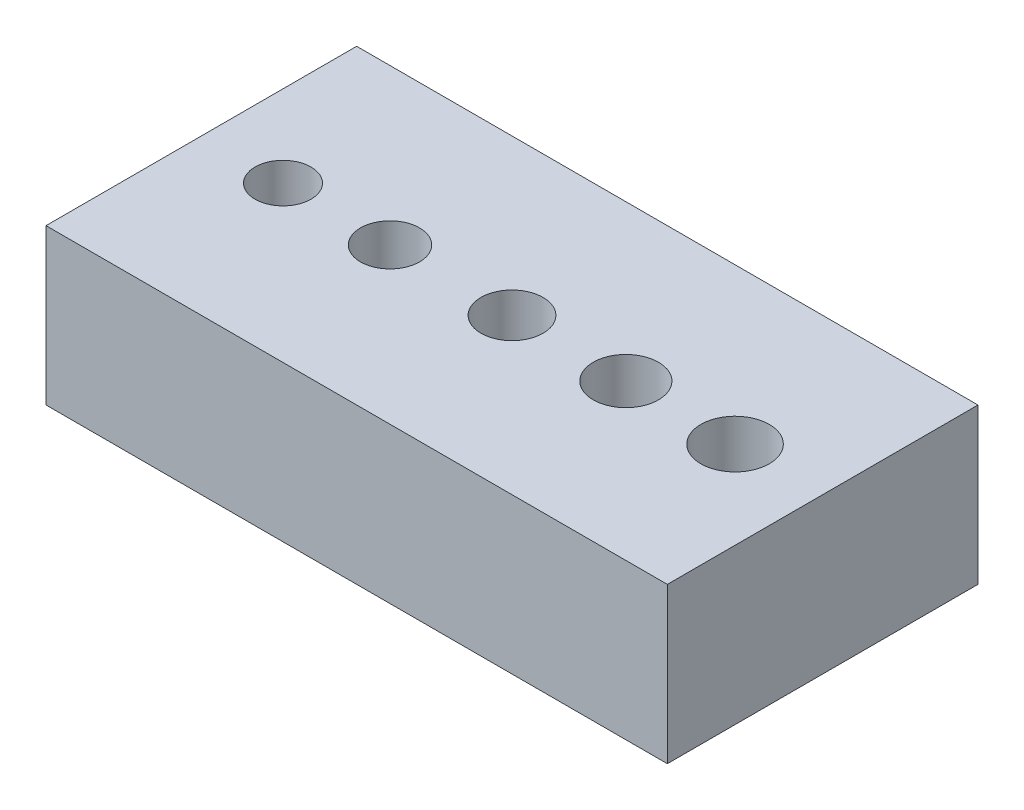
SolidWorks part; units mm, degrees
ref_plane "前视基准面" through (0, 0, 0) normal (0, 0, 1) x (1, 0, 0)
ref_plane "上视基准面" through (0, 0, 0) normal (0, 1, 0) x (1, 0, 0)
ref_plane "右视基准面" through (0, 0, 0) normal (1, 0, 0) x (0, 0, -1)
other "Configuration Table"
sketch "草图1" plane through (0, 0, 0) normal (0, 1, 0) x (1, 0, 0)
  line L1 (-10, 5) -> (10, 5)
  line L2 (-10, 5) -> (-10, -5)
  line L3 (-10, -5) -> (10, -5)
  line L4 (10, 5) -> (10, -5)
  line L5 (-10, 5) -> (10, -5) construction
  line L6 (-10, -5) -> (10, 5) construction
  circle A0 centre (0, 0) radius 1
  circle A1 centre (-3.9269, 0) radius 0.95
  circle A2 centre (3.6651, 0) radius 1.05
  circle A3 centre (7.1799, 0) radius 1.1
  circle A4 centre (-7.3714, 0) radius 0.9
  point P0 (0, 0)
  point P16 (-3.9269, 0)
  point P17 (-7.3714, 0)
  point P18 (0, 0)
  dimension "D3" = 2
  dimension "D4" = 2.1
  dimension "D5" = 2.2
  dimension "D6" = 1.9
  dimension "D7" = 1.8
  dimension "D1" = 20
  dimension "D2" = 10
extrude "凸台-拉伸1" add sketch "草图1" along normal blind 5
